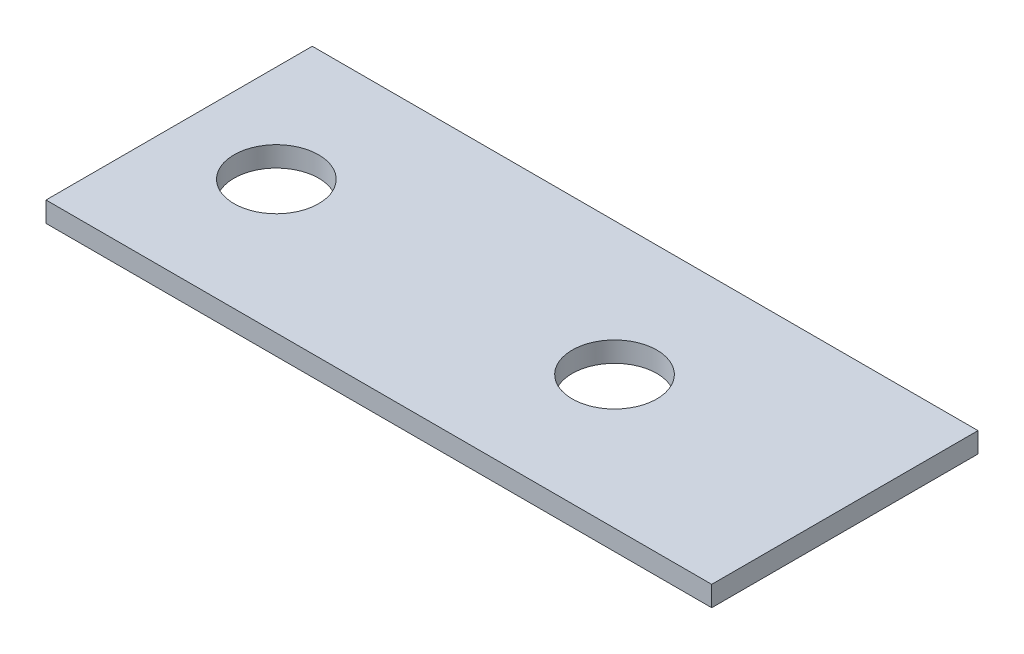
SolidWorks part; units mm, degrees
ref_plane "Front Plane" through (0, 0, 0) normal (0, 0, 1) x (1, 0, 0)
ref_plane "Top Plane" through (0, 0, 0) normal (0, 1, 0) x (1, 0, 0)
ref_plane "Right Plane" through (0, 0, 0) normal (1, 0, 0) x (0, 0, -1)
sketch "Sketch1" plane through (0, 0, 0) normal (0, 1, 0) x (1, 0, 0)
  line L0 (0, 0) -> (12.7, 0) construction
  line L1 (-3.65, 5) -> (16.35, 5)
  line L2 (-3.65, 5) -> (-3.65, -5)
  line L3 (-3.65, -5) -> (16.35, -5)
  line L4 (16.35, 5) -> (16.35, -5)
  line L6 (16.35, 5) -> (21.35, 5)
  line L7 (16.35, 5) -> (16.35, -5)
  line L8 (16.35, -5) -> (21.35, -5)
  line L9 (21.35, 5) -> (21.35, -5)
  circle A0 centre (0, 0) radius 1.59
  circle A1 centre (12.7, 0) radius 1.59
  point P6 (16.35, 0)
  point P11 (6.35, 5)
  point P12 (6.35, 0)
  dimension "D1" = 3.18
  dimension "D2" = 20
  dimension "D3" = 12.7
  dimension "D4" = 10
  dimension "D5" = 5
extrude "Boss-Extrude1" add sketch "Sketch1" along normal blind 0.762
